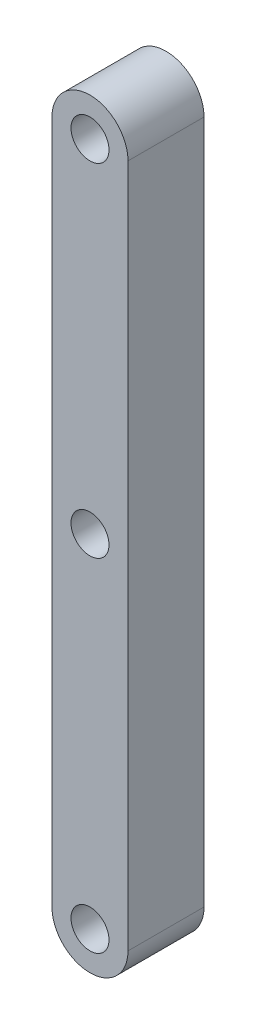
SolidWorks part; units mm, degrees
ref_plane "前视基准面" through (0, 0, 0) normal (0, 0, 1) x (1, 0, 0)
ref_plane "上视基准面" through (0, 0, 0) normal (0, 1, 0) x (1, 0, 0)
ref_plane "右视基准面" through (0, 0, 0) normal (1, 0, 0) x (0, 0, -1)
sketch "草图1" plane through (0, 0, 0) normal (0, 0, 1) x (1, 0, 0)
  line L0 (0, 0) -> (0, 90) construction
  line L5 (-5, 0) -> (-5, 90)
  line L6 (5, 0) -> (5, 90)
  arc A0 (-5, 0) -> (5, 0) centre (0, 0) ccw
  arc A1 (5, 90) -> (-5, 90) centre (0, 90) ccw
  point P2 (0, 45)
  dimension "D1" = 90
  dimension "D2" = 10
extrude "凸台-拉伸1" add sketch "草图1" along normal blind 10
sketch "草图3" plane through (0, 0, 0) normal (0, 0, -1) x (-1, 0, 0)
  circle A0 centre (0, 45) radius 2.5
  dimension "D2" = 5
extrude "切除-拉伸1" cut sketch "草图3" against normal blind 10
sketch "草图4" plane through (0, 0, 10) normal (0, 0, 1) x (1, 0, 0)
  circle A6 centre (0, 90) radius 2.5
extrude "切除-拉伸2" cut sketch "草图4" against normal blind 10
sketch "草图5" plane through (0, 0, 10) normal (0, 0, 1) x (1, 0, 0)
  circle A2 centre (0, 0) radius 2.5
extrude "切除-拉伸3" cut sketch "草图5" against normal blind 10
sketch "草图6" plane through (0, 0, 0) normal (0, 0, -1) x (-1, 0, 0)
  circle A1 centre (0, 45) radius 2.5 construction
  circle A4 centre (0, 45) radius 2.5
